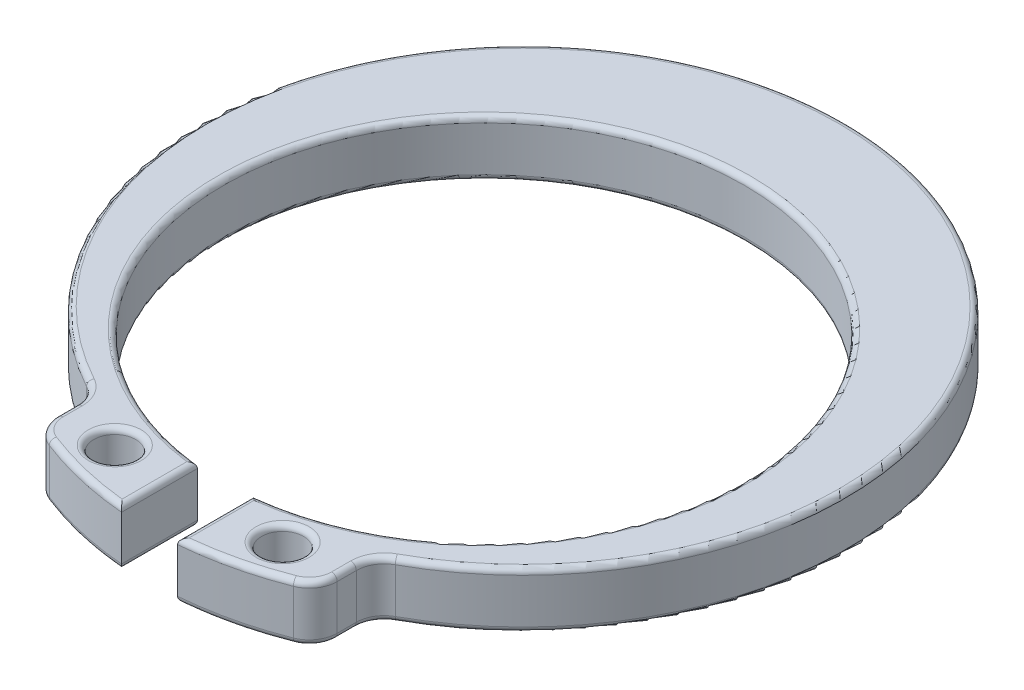
SolidWorks part; units mm, degrees
ref_plane "前视基准面" through (0, 0, 0) normal (0, 0, 1) x (1, 0, 0)
ref_plane "上视基准面" through (0, 0, 0) normal (0, 1, 0) x (1, 0, 0)
ref_plane "右视基准面" through (0, 0, 0) normal (1, 0, 0) x (0, 0, -1)
other "Configuration Table"
sketch "草图1" plane through (0, 0, 0) normal (0, 1, 0) x (1, 0, 0)
  line L0 (-1.4772, 0) -> (2.5, 0) construction
  line L1 (0, 6.9341) -> (0, -8.0856) construction
  line L2 (0.5, -4.623) -> (0.5, -5.9791)
  line L3 (2.5, -4.4781) -> (2.5, -5.4544)
  line L4 (-2.5, -4.4781) -> (-2.5, -5.4544)
  line L5 (-0.5, -4.623) -> (-0.5, -5.9791)
  arc A0 (0.5, -4.623) -> (-0.5, -4.623) centre (0, 0) ccw
  arc A1 (2.5, -4.4781) -> (-2.5, -4.4781) centre (0, 0.7) ccw
  arc A2 (0.5, -5.9791) -> (2.5, -5.4544) centre (0, 0) ccw
  arc A3 (-0.5, -5.9791) -> (-2.5, -5.4544) centre (0, 0) cw
  circle A4 centre (1.5, -5.1) radius 0.375
  circle A5 centre (-1.5, -5.1) radius 0.375
  dimension "D1" = 9.3
  dimension "D2" = 11.5
  dimension "D6" = 6
  dimension "D7" = 0.75
  dimension "D3" = 0.7
  dimension "D4" = 0.5
  dimension "D5" = 2
  dimension "D8" = 1.5
  dimension "D9" = 5.1
extrude "凸台-拉伸1" add sketch "草图1" along normal blind 1
fillet "圆角1" radius 0.5 4 edges at (-2.5, 0.5, 5.4544) (-2.5, 0.5, 4.4781) (2.5, 0.5, 5.4544) (2.5, 0.5, 4.4781)
fillet "圆角2" radius 0.1 28 edges at (-1.5, 0, 4.725) (1.5, 0, 5.475) (-0.5, 0, 5.3011) (0, 0, -4.65) (0.5, 0, 5.3011) (1.355, 0, 5.845) (2.4129, 0, 5.4055) (2.5, 0, 4.9532) (2.5699, 0, 4.528) (0, 0, -6.45) (-2.5699, 0, 4.528) (-2.5, 0, 4.9532) (-2.4129, 0, 5.4055) (-1.355, 0, 5.845) (-1.5, 1, 4.725) (-2.5699, 1, 4.528) (0, 1, -6.45) (2.5699, 1, 4.528) (2.5, 1, 4.9532) (2.4129, 1, 5.4055) (1.355, 1, 5.845) (0.5, 1, 5.3011) (0, 1, -4.65) (-0.5, 1, 5.3011) (-1.355, 1, 5.845) (-2.4129, 1, 5.4055) (-2.5, 1, 4.9532) (1.5, 1, 5.475)
